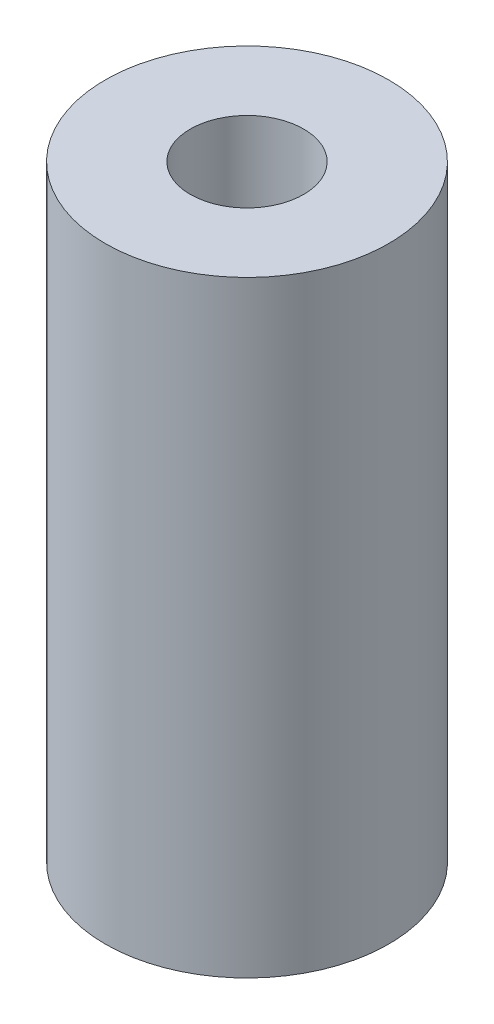
SolidWorks part; units mm, degrees
ref_plane "Front Plane" through (0, 0, 0) normal (0, 0, 1) x (1, 0, 0)
ref_plane "Top Plane" through (0, 0, 0) normal (0, 1, 0) x (1, 0, 0)
ref_plane "Right Plane" through (0, 0, 0) normal (1, 0, 0) x (0, 0, -1)
sketch "Sketch1" plane through (0, 0, 0) normal (0, 1, 0) x (1, 0, 0)
  circle A0 centre (0, 0) radius 2.54
  circle A1 centre (0, 0) radius 6.35
  dimension "D1" = 5.08
  dimension "D2" = 12.7
extrude "Boss-Extrude1" add sketch "Sketch1" along normal blind 27.178
